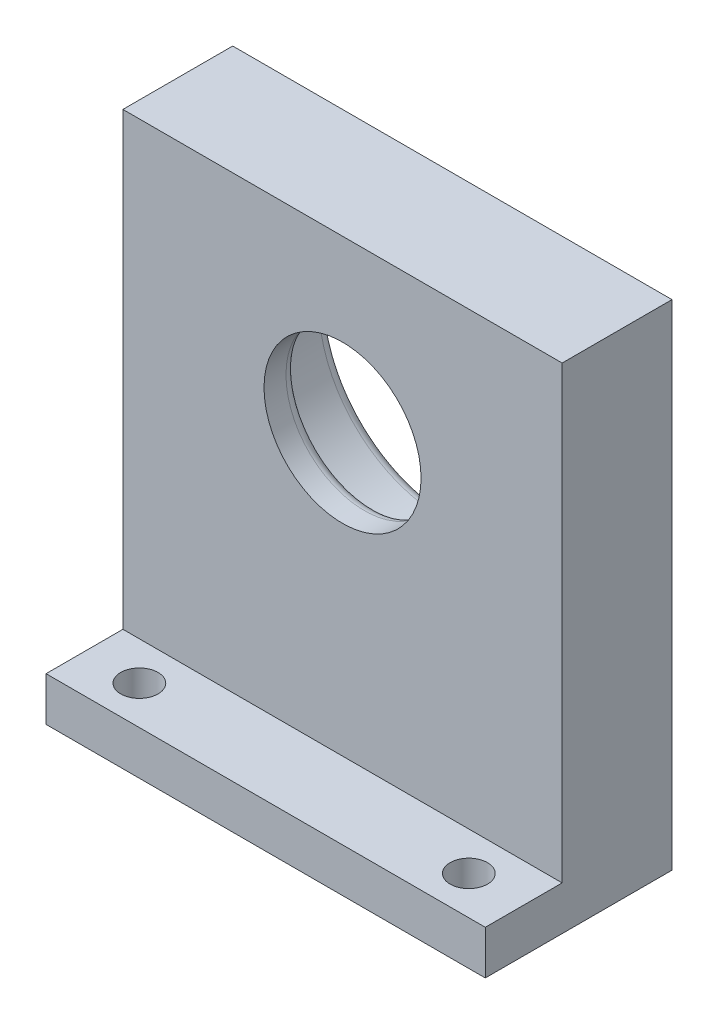
SolidWorks part; units mm, degrees
ref_plane "Front Plane" through (0, 0, 0) normal (0, 0, 1) x (1, 0, 0)
ref_plane "Top Plane" through (0, 0, 0) normal (0, 1, 0) x (1, 0, 0)
ref_plane "Right Plane" through (0, 0, 0) normal (1, 0, 0) x (0, 0, -1)
other "Configuration Table"
sketch "Sketch1" plane through (0, 0, 0) normal (0, 0, 1) x (1, 0, 0)
  line L0 (0, -22.5) -> (0, 7) construction
  line L1 (-20, -22.5) -> (20, -22.5)
  line L2 (-20, -22.5) -> (-20, 22.5)
  line L3 (-20, 22.5) -> (20, 22.5)
  line L4 (20, -22.5) -> (20, 22.5)
  line L5 (-20, -22.5) -> (20, 22.5) construction
  line L6 (-20, 22.5) -> (20, -22.5) construction
  circle A0 centre (0, 7) radius 4 construction
  circle A1 centre (0, 7) radius 11.15
  point P0 (0, 0)
  dimension "D4" = 8
  dimension "D5" = 22.3
  dimension "D1" = 45
  dimension "D2" = 40
  dimension "D3" = 29.5
extrude "Boss-Extrude1" add sketch "Sketch1" along normal blind 7
sketch "Sketch2" plane through (0, 0, 7) normal (0, 0, 1) x (1, 0, 0)
  line L0 (20, 22.5) -> (-20, 22.5) construction
  line L1 (-20, 22.5) -> (-20, -22.5) construction
  line L2 (-20, -22.5) -> (20, -22.5) construction
  line L3 (20, -22.5) -> (20, 22.5) construction
  line L4 (20, 22.5) -> (-20, 22.5)
  line L5 (-20, 22.5) -> (-20, -22.5)
  line L6 (-20, -22.5) -> (20, -22.5)
  line L7 (20, -22.5) -> (20, 22.5)
  circle A3 centre (0, 7) radius 7.15
  circle A4 centre (0, 7) radius 7.15
  dimension "D1" = 4
extrude "Boss-Extrude2" add sketch "Sketch2" along normal blind 3
fillet "Fillet1" radius 1 2 edges at (11.15, 7, 0) (7.15, 7, 7)
sketch "Sketch3" plane through (0, 0, 10) normal (0, 0, 1) x (1, 0, 0)
  line L0 (-20, -22.5) -> (20, -22.5) construction
  line L1 (-20, -22.5) -> (20, -22.5)
  line L2 (-20, -22.5) -> (-20, -18.5)
  line L3 (-20, 22.5) -> (-20, -22.5) construction
  line L4 (-20, -18.5) -> (20, -18.5)
  line L5 (20, -22.5) -> (20, 22.5) construction
  line L6 (20, -18.5) -> (20, -22.5)
  dimension "D1" = 4
extrude "Boss-Extrude3" add sketch "Sketch3" along normal blind 7
sketch "Sketch4" plane through (0, -18.5, 0) normal (0, 1, 0) x (1, 0, 0)
  line L0 (-20, -17) -> (-20, -10) construction
  line L1 (20, -10) -> (-20, -10) construction
  line L2 (20, -17) -> (20, -10) construction
  line L3 (20, -17) -> (-20, -17) construction
  line L4 (-20, -17) -> (-20, -10) construction
  line L5 (20, -10) -> (-20, -10) construction
  line L6 (20, -17) -> (20, -10) construction
  line L7 (20, -17) -> (-20, -17) construction
  line L8 (-20, -13.5) -> (20, -13.5) construction
  circle A0 centre (-15, -13.5) radius 1.7
  circle A1 centre (15, -13.5) radius 1.7
  point P8 (0, 0)
  dimension "D1" = 3.4
  dimension "D2" = 5
  dimension "D3" = 5
extrude "Cut-Extrude1" cut sketch "Sketch4" against normal through all
